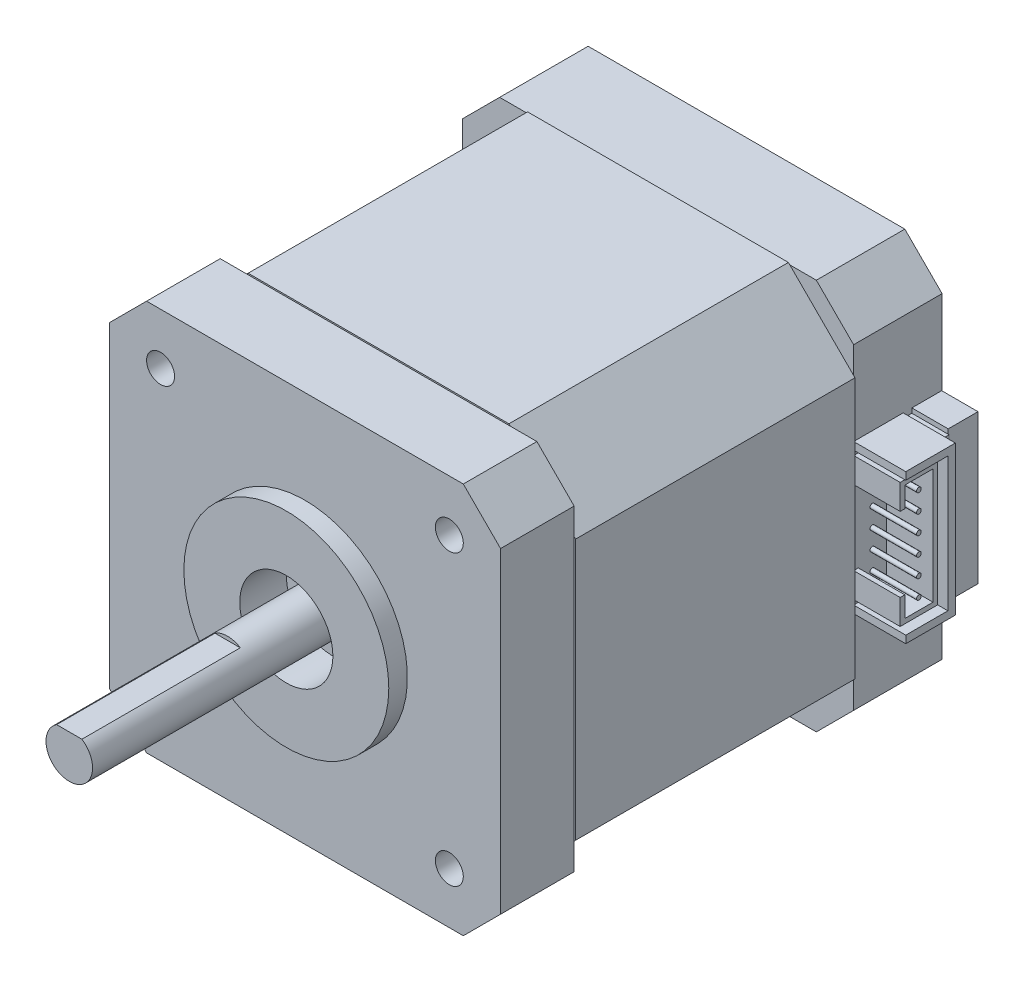
SolidWorks part; units mm, degrees
ref_plane "Front Plane" through (0, 0, 0) normal (0, 0, 1) x (1, 0, 0)
ref_plane "Top Plane" through (0, 0, 0) normal (0, 1, 0) x (1, 0, 0)
ref_plane "Right Plane" through (0, 0, 0) normal (1, 0, 0) x (0, 0, -1)
sketch "Sketch1" plane through (0, 0, 0) normal (0, 0, 1) x (1, 0, 0)
  line L0 (-17, 21) -> (-21, 17)
  line L1 (-17, -21) -> (17, -21)
  line L2 (-21, -17) -> (-21, 17)
  line L3 (-17, 21) -> (17, 21)
  line L4 (21, -17) -> (21, 17)
  line L5 (21, 17) -> (17, 21)
  line L6 (17, -21) -> (21, -17)
  line L12 (-21, -17) -> (-17, -21)
  point P0 (0, 0)
  point P15 (0, 0)
  dimension "D1" = 4
extrude "Boss-Extrude1" add sketch "Sketch1" along normal blind 9.5
sketch "Sketch2" plane through (0, 0, 9.5) normal (0, 0, 1) x (1, 0, 0)
  line L0 (14, 21.15) -> (21.15, 14)
  line L5 (-14, -21.15) -> (14, -21.15)
  line L6 (-21.15, -14) -> (-21.15, 14)
  line L7 (-14, 21.15) -> (14, 21.15)
  line L12 (21.15, -14) -> (21.15, 14)
  line L14 (17.5, -17.5) -> (17.575, -17.575) construction
  line L15 (-21.15, 14) -> (-14, 21.15)
  line L16 (21.15, -14) -> (14, -21.15)
  line L17 (-14, -21.15) -> (-21.15, -14)
  line L18 (17.5, 17.5) -> (17.575, 17.575) construction
  point P0 (0, 0)
  point P1 (0, 0)
  point P13 (0, 0)
  point P16 (0, 0)
  point P19 (0, 0)
  point P22 (0, 0)
  point P29 (0, 0)
  dimension "D1" = 4
  dimension "D5" = 4
extrude "Boss-Extrude2" add sketch "Sketch2" along normal blind 30
sketch "Sketch3" plane through (0, 0, 39.5) normal (0, 0, 1) x (1, 0, 0)
  line L0 (-17, 21) -> (17, 21)
  line L1 (17, 21) -> (21, 17)
  line L2 (21, 17) -> (21, -17)
  line L3 (21, -17) -> (17, -21)
  line L4 (17, -21) -> (-17, -21)
  line L5 (-17, -21) -> (-21, -17)
  line L6 (-21, -17) -> (-21, 17)
  line L7 (-21, 17) -> (-17, 21)
extrude "Boss-Extrude3" add sketch "Sketch3" along normal blind 7.9
sketch "Sketch5" plane through (0, 0, 47.4) normal (0, 0, 1) x (1, 0, 0)
  circle A0 centre (0, 0) radius 11
  circle A1 centre (0, 0) radius 5
  dimension "D1" = 22
  dimension "D2" = 10
extrude "Boss-Extrude4" add sketch "Sketch5" along normal blind 2
sketch "Sketch6" plane through (0, 0, 47.4) normal (0, 0, 1) x (1, 0, 0)
  circle A0 centre (0, 0) radius 5
extrude "Cut-Extrude1" cut sketch "Sketch6" against normal blind 3
sketch "Sketch7" plane through (0, 0, 44.4) normal (0, 0, 1) x (1, 0, 0)
  circle A0 centre (0, 0) radius 2.5
  dimension "D1" = 5
extrude "Boss-Extrude5" add sketch "Sketch7" along normal up to surface (5 mm away) up to face at (11, 0, 49.4)
sketch "Sketch8" plane through (0, 0, 49.4) normal (0, 0, 1) x (1, 0, 0)
  circle A0 centre (0, 0) radius 2.5
extrude "Boss-Extrude6" add sketch "Sketch8" along normal blind 23.3
sketch "Sketch9" plane through (0, 0, 72.7) normal (0, 0, 1) x (1, 0, 0)
  line L0 (-2.3166, 2.1) -> (3.6979, 2.1)
  line L1 (3.6979, 2.1) -> (-0.1236, 3.991)
  line L2 (-0.1236, 3.991) -> (-2.3166, 2.1)
extrude "Cut-Extrude2" cut sketch "Sketch9" against normal blind 17
sketch "Sketch10" plane through (0, 21.15, 0) normal (0, 1, 0) x (1, 0, 0)
  line L1 (-13, -13.6909) -> (13, -13.6909)
  line L3 (-13, -27.8113) -> (13, -27.8113)
  line L6 (-13, -13.6909) -> (-13, -27.8113)
  line L8 (13, -13.6909) -> (13, -27.8113)
extrude "Boss-Extrude7" [suppressed] add sketch "Sketch10" along normal blind 0.01
sketch "Sketch11" plane through (21, 0, 0) normal (1, 0, 0) x (0, 0, -1)
  line L1 (-3.2456, -8) -> (-0.0456, -8)
  line L3 (-3.2456, 8) -> (-0.0456, 8)
  line L5 (-3.2456, 8) -> (-3.2456, -8)
  line L7 (-0.0456, 8) -> (-0.0456, -8)
  point P0 (0, 0)
  dimension "D2" = 3.2
extrude "Boss-Extrude8" add sketch "Sketch11" along normal blind 3.9
sketch "Sketch12" plane through (21, 0, 0) normal (1, 0, 0) x (0, 0, -1)
  line L0 (-9.5, -14.15) -> (-9.5, 14.15) construction
  line L2 (-9.5, 7.479) -> (-9.5, 7.2)
  line L5 (-0.0456, 8) -> (-3.2456, 8) construction
  line L6 (-9.5, 7.2) -> (-4.9761, 7.2)
  line L9 (-4.1761, 7.2) -> (-4.1761, -7.2)
  line L10 (-4.1761, 8) -> (-9.5, 8)
  line L11 (-9.5, -14) -> (-9.5, 14) construction
  line L12 (-9.5, 7.479) -> (-9.5, 7.2)
  line L13 (-0.0456, 0) -> (6.3047, 0) construction
  line L14 (-0.0456, -8) -> (-0.0456, 8) construction
  line L15 (-9.5, -7.2) -> (-4.9761, -7.2)
  line L16 (-9.5, 7.2) -> (-9.5, 8)
  line L17 (-9.5, -7.2) -> (-9.5, -8)
  line L19 (-4.1761, -8) -> (-9.5, -8)
  line L20 (-4.9761, 7.2) -> (-4.9761, -7.2)
  line L21 (-4.1761, 8) -> (-4.1761, 7.2)
  line L22 (-4.1761, -7.2) -> (-4.1761, -8)
  dimension "D1" = 0.8
  dimension "D2" = 0.8
extrude "Boss-Extrude9" add sketch "Sketch12" along normal blind 5.6 contours L16 L10 L21 L9 L22 L19 L17 L15 L20 L6
sketch "Sketch13" plane through (21, 0, 0) normal (1, 0, 0) x (0, 0, -1)
  line L0 (-4.1761, 8) -> (-4.1761, -8) construction
  line L1 (-4.1761, 7.5) -> (-3.2456, 7.5)
  line L2 (-4.1761, 7.5) -> (-4.1761, -7.5)
  line L3 (-4.1761, -7.5) -> (-3.2456, -7.5)
  line L4 (-3.2456, 7.5) -> (-3.2456, -7.5)
  line L5 (-3.2456, 8) -> (-3.2456, -8) construction
  line L6 (-0.0456, 8) -> (-3.2456, 8) construction
  line L7 (-3.2456, -8) -> (-0.0456, -8) construction
  dimension "D1" = 0.5
  dimension "D2" = 0.5
extrude "Boss-Extrude10" add sketch "Sketch13" along normal up to surface (3.9 mm away) up to face at (24.9, 0, 1.6456)
sketch "Sketch14" plane through (24.9, 0, 0) normal (1, 0, 0) x (0, 0, -1)
  line L1 (-4.1761, 7.5) -> (-3.2456, 7.5)
  line L2 (-4.1761, 7.5) -> (-4.1761, -7.5)
  line L3 (-4.1761, -7.5) -> (-3.2456, -7.5)
  line L4 (-3.2456, 7.5) -> (-3.2456, -7.5)
extrude "Boss-Extrude11" add sketch "Sketch14" along normal blind 0.1
sketch "Sketch15" plane through (21, 0, 0) normal (1, 0, 0) x (0, 0, -1)
  line L0 (-5.9761, 6.2) -> (-9, 6.2)
  line L5 (0, 0) -> (5.9447, 0) construction
  line L6 (-9.5, -7.2) -> (-9.5, 7.2) construction
  line L7 (-9.5, 4) -> (-9, 4)
  line L9 (-9.5, -4) -> (-9, -4)
  line L11 (-9.5, 7.2) -> (-4.9761, 7.2) construction
  line L12 (-9, 6.7) -> (-5.4761, 6.7)
  line L13 (-9, 6.2) -> (-9, 4)
  line L14 (-9, -6.7) -> (-5.4761, -6.7)
  line L15 (-5.4761, 6.7) -> (-5.4761, -6.7)
  line L16 (-4.9761, 7.2) -> (-4.9761, -7.2) construction
  line L17 (-9, 6.7) -> (-9.5, 6.7)
  line L18 (-9.5, -7.2) -> (-9.5, 7.2) construction
  line L19 (-9.5, 6.7) -> (-9.5, 4)
  line L20 (-5.9761, 6.2) -> (-5.9761, -6.2)
  line L21 (-9.5, -7.2) -> (-4.9761, -7.2) construction
  line L22 (-9, -6.2) -> (-5.9761, -6.2)
  line L23 (-9.5, -4) -> (-9.5, -6.7)
  line L24 (-9.5, -6.7) -> (-9, -6.7)
  line L25 (-9, -4) -> (-9, -6.2)
  dimension "D1" = 4
  dimension "D2" = 4
  dimension "D4" = 0.5
  dimension "D5" = 0.5
  dimension "D6" = 0.5
  dimension "D7" = 0.5
  dimension "D8" = 0.5
  dimension "D9" = 0.5
extrude "Boss-Extrude12" add sketch "Sketch15" along normal blind 5
sketch "Sketch16" plane through (21, 0, 0) normal (1, 0, 0) x (0, 0, -1)
  line L0 (-7.4881, 6.2) -> (-7.4881, 5) construction
  line L1 (-9, 6.2) -> (-5.9761, 6.2) construction
  circle A0 centre (-7.4881, 5) radius 0.25
  circle A1 centre (-7.4881, 3) radius 0.25
  circle A2 centre (-7.4881, 1) radius 0.25
  circle A3 centre (-7.4881, -1) radius 0.25
  circle A4 centre (-7.4881, -3) radius 0.25
  circle A5 centre (-7.4881, -5) radius 0.25
  dimension "D2" = 0.5
  dimension "D1" = 1.2
  dimension "D3" = 6
extrude "Boss-Extrude13" add sketch "Sketch16" along normal blind 5
sketch "Sketch17" plane through (0, 0, 47.4) normal (0, 0, 1) x (1, 0, 0)
  circle A0 centre (-15.5, 15.5) radius 1.5
  circle A1 centre (15.5, 15.5) radius 1.5
  circle A2 centre (15.5, -15.5) radius 1.5
  circle A3 centre (-15.5, -15.5) radius 1.5
  point P0 (0, 0)
  point P13 (0, 0)
  dimension "D3" = 3
  dimension "D1" = 4
extrude "Cut-Extrude3" cut sketch "Sketch17" against normal blind 5.5
sketch "Sketch18" plane through (0, 0, 0) normal (0, 0, -1) x (-1, 0, 0)
  circle A0 centre (-15.5, 15.5) radius 3.25
  circle A1 centre (15.5, 15.5) radius 3.25
  circle A2 centre (15.5, -15.5) radius 3.25
  circle A3 centre (-15.5, -15.5) radius 3.25
  point P0 (0, 0)
  point P13 (0, 0)
  dimension "D3" = 6.5
  dimension "D1" = 4
extrude "Cut-Extrude4" cut sketch "Sketch18" against normal blind 3
sketch "Sketch20" plane through (0, 0, 3) normal (0, 0, -1) x (-1, 0, 0)
  circle A0 centre (-15.5, 15.5) radius 1.5
  circle A1 centre (15.5, 15.5) radius 1.5
  circle A2 centre (-15.5, -15.5) radius 1.5
  circle A3 centre (15.5, -15.5) radius 1.5
  dimension "D1" = 3
  dimension "D2" = 3
  dimension "D3" = 3
  dimension "D4" = 3
extrude "Cut-Extrude5" cut sketch "Sketch20" against normal blind 4
sketch "Sketch21" plane through (0, 0, 0) normal (0, 0, -1) x (-1, 0, 0)
  circle A0 centre (0, 0) radius 4.5
  dimension "D1" = 9
extrude "Cut-Extrude6" cut sketch "Sketch21" against normal blind 4
